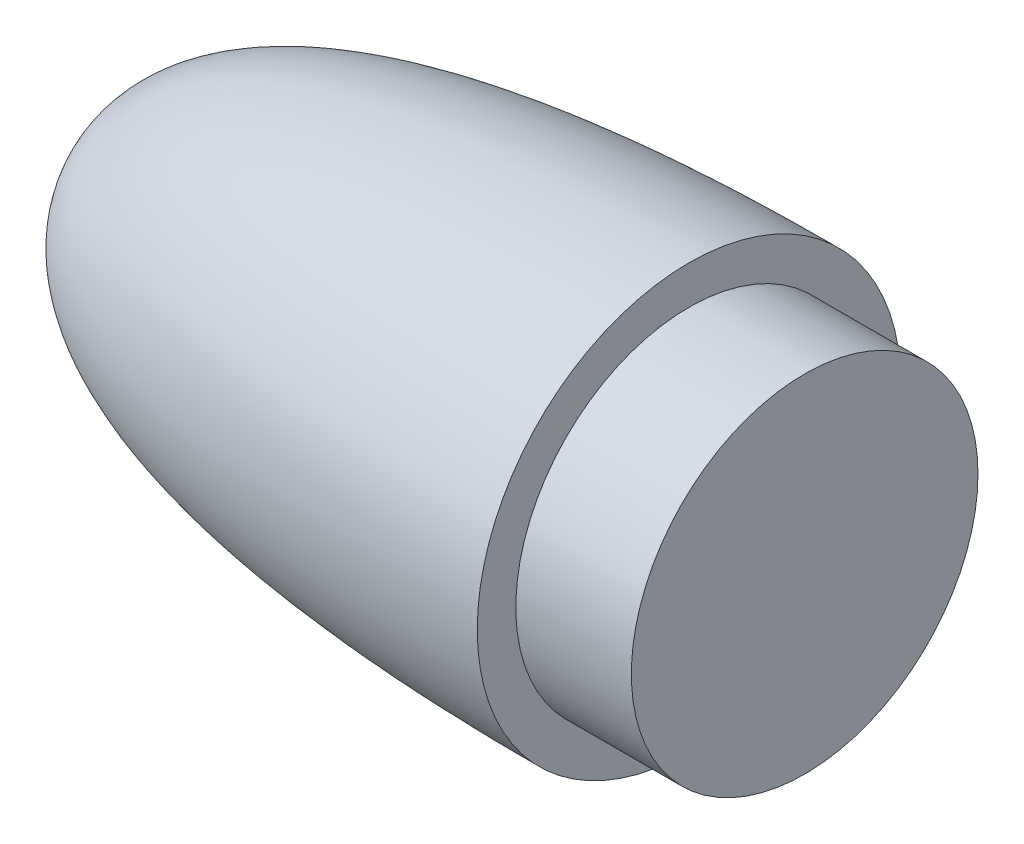
SolidWorks part; units mm, degrees
ref_plane "Front Plane" through (0, 0, 0) normal (0, 0, 1) x (1, 0, 0)
ref_plane "Top Plane" through (0, 0, 0) normal (0, 1, 0) x (1, 0, 0)
ref_plane "Right Plane" through (0, 0, 0) normal (1, 0, 0) x (0, 0, -1)
sketch "Sketch1" plane through (0, 0, 0) normal (0, 1, 0) x (1, 0, 0)
  line L0 (-15, 0) -> (-15, -5)
  line L1 (0, 0) -> (-15, 0)
  line L2 (0, 0) -> (0, 45)
  line L3 (0, 45) -> (-15, 45)
  line L4 (-15, 0) -> (-15, 45)
  line L5 (-15, 45) -> (-15, 50)
  line L6 (-15, 22.5) -> (-91.2, 22.5)
  line L7 (-15, -5) -> (-91.2, -5) construction
  line L8 (-91.2, -5) -> (-91.2, 22.5) construction
  line L9 (-15, 50) -> (-91.2, 50) construction
  line L10 (-91.2, 50) -> (-91.2, 22.5) construction
  line L11 (-15, 22.5) -> (0, 22.5)
  spline S0 degree 2 poles (-15, -5) (-91.2, -5) (-91.2, 22.5) knots 0 0 0 1 1 1
  spline S1 degree 2 poles (-15, 50) (-91.2, 50) (-91.2, 22.5) knots 0 0 0 1 1 1
  dimension "D1" = 45
  dimension "D2" = 15
  dimension "D3" = 5
  dimension "D4" = 5
  dimension "D5" = 76.2
revolve "Revolve2" add sketch "Sketch1" angle 360 about L6
